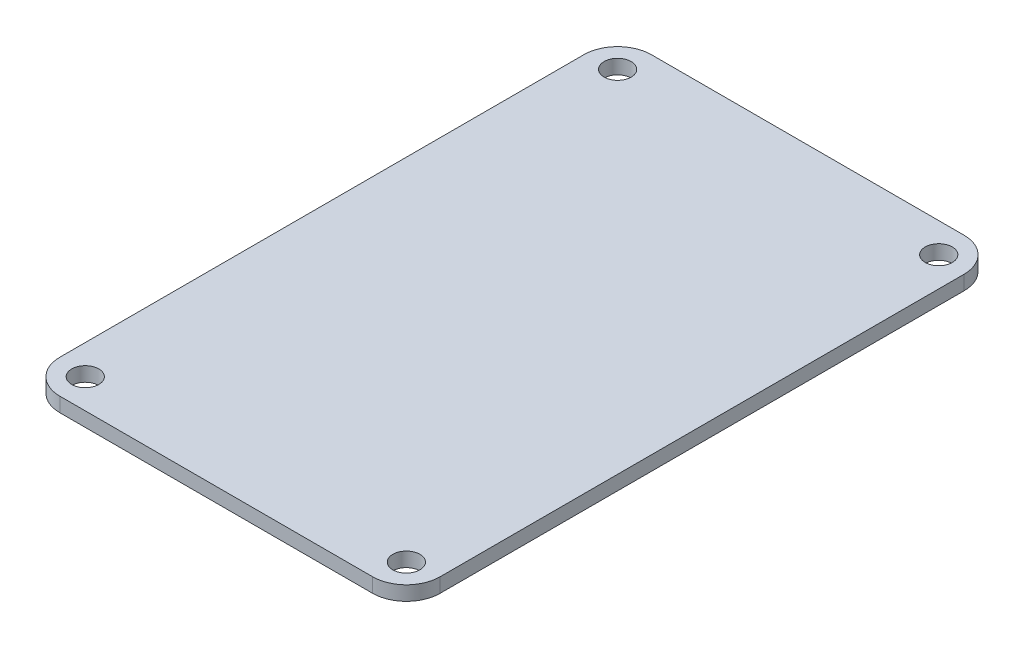
SolidWorks part; units mm, degrees
ref_plane "Front Plane" through (0, 0, 0) normal (0, 0, 1) x (1, 0, 0)
ref_plane "Top Plane" through (0, 0, 0) normal (0, 1, 0) x (1, 0, 0)
ref_plane "Right Plane" through (0, 0, 0) normal (1, 0, 0) x (0, 0, -1)
sketch "Sketch1" plane through (0, 0, 0) normal (0, 1, 0) x (1, 0, 0)
  line L1 (-22.5, 35) -> (22.5, 35)
  line L2 (-22.5, 35) -> (-22.5, -35)
  line L3 (-22.5, -35) -> (22.5, -35)
  line L4 (22.5, 35) -> (22.5, -35)
  line L5 (-22.5, 35) -> (22.5, -35) construction
  line L6 (-22.5, -35) -> (22.5, 35) construction
  point P0 (0, 0)
  dimension "D1" = 45
  dimension "D2" = 70
extrude "MAIN BODY" add sketch "Sketch1" along normal blind 1.7
hole_wizard "M3 Clearance Hole1" positions "Sketch2" profile "Sketch3" hole size "M3" standard "ANSI Metric" end condition through all
sketch "Sketch2" plane through (0, 1.7, 0) normal (0, 1, 0) x (1, 0, 0)
  line L0 (-22.5, 35) -> (-22.5, -35) construction
  line L1 (22.5, 35) -> (-22.5, 35) construction
  point P0 (-19, 31.5)
  dimension "D1" = 3.5
  dimension "D2" = 3.5
sketch "Sketch3" plane through (-19, 1.7, -31.5) normal (1, 0, 0) x (0, 0, 1)
  line L0 (0, 0) -> (0, 1.7)
  line L1 (0, 1.7) -> (1.6, 1.7)
  line L2 (1.6, 1.7) -> (1.6, 0)
  line L5 (1.6, 0) -> (0, 0)
  line L11 (0, -6.35) -> (0, 107.95) construction
  dimension "Thru Hole Dia." = 3.2
  dimension "Thru Hole Depth" = 1.7
mirror "Mirror1" about plane through (0, 0, 0) normal (1, 0, 0) of "M3 Clearance Hole1"
mirror "Mirror2" about plane through (0, 0, 0) normal (0, 0, 1) of "Mirror1", "M3 Clearance Hole1"
fillet "Fillet1" radius 4 4 edges at (-22.5, 0.85, -35) (22.5, 0.85, -35) (22.5, 0.85, 35) (-22.5, 0.85, 35)
